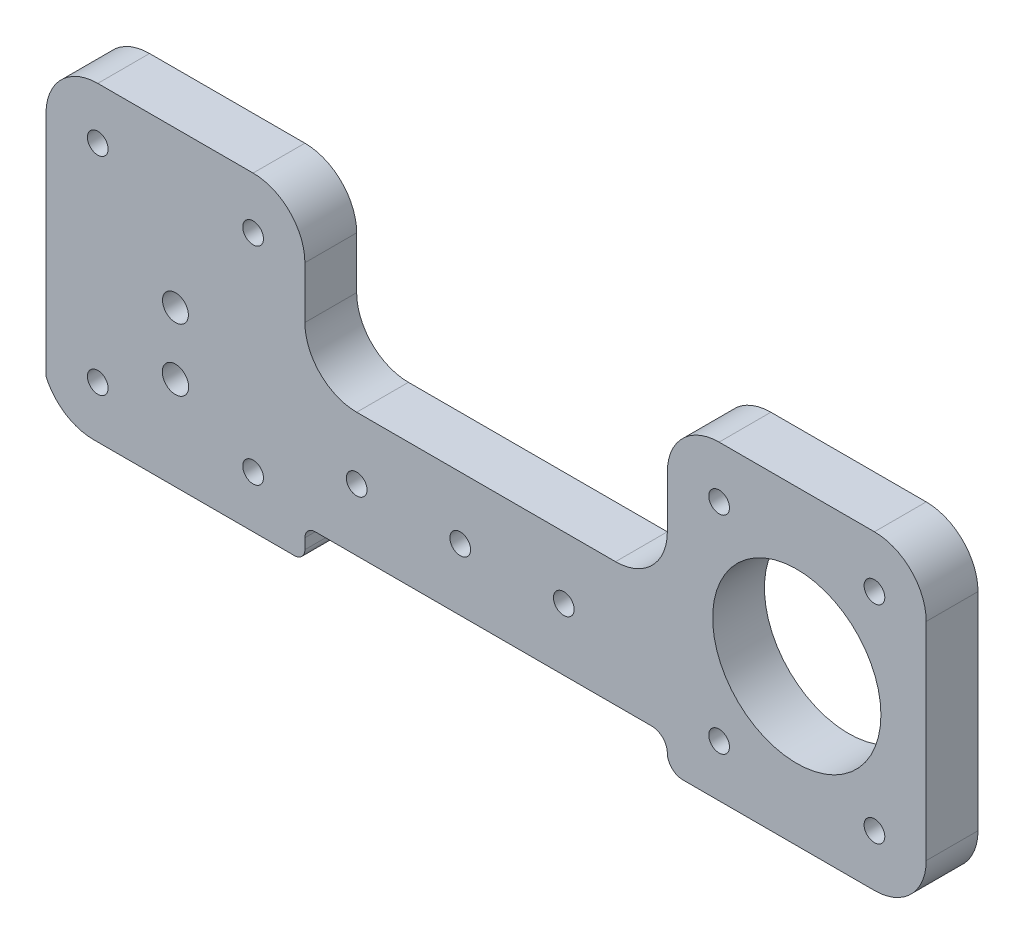
SolidWorks part; units mm, degrees
ref_plane "Front Plane" through (0, 0, 0) normal (0, 0, 1) x (1, 0, 0)
ref_plane "Top Plane" through (0, 0, 0) normal (0, 1, 0) x (1, 0, 0)
ref_plane "Right Plane" through (0, 0, 0) normal (1, 0, 0) x (0, 0, -1)
sketch "Model" plane through (0, 0, 0) normal (0, 0, 1) x (1, 0, 0)
  line L0 (-13.0894, 50) -> (-13.0894, 6)
  line L1 (26.9106, 60) -> (-3.0894, 60)
  line L2 (36.9106, 40) -> (36.9106, 50)
  line L3 (96.9106, 30) -> (46.9106, 30)
  line L4 (106.9106, 50) -> (106.9106, 40)
  line L5 (146.9106, 60) -> (116.9106, 60)
  line L6 (156.9106, 10) -> (156.9106, 50)
  line L7 (109.9106, 0) -> (146.9106, 0)
  line L8 (38.9106, 6) -> (103.9106, 6)
  line L9 (36.9106, 2) -> (36.9106, 4)
  line L10 (-3.9243, 0) -> (34.9106, 0)
  circle A0 centre (26.9106, 50) radius 2
  circle A1 centre (26.9106, 10) radius 2
  circle A2 centre (11.9106, 30) radius 2.5
  circle A3 centre (146.9106, 50) radius 2
  circle A4 centre (86.9106, 18) radius 2
  circle A5 centre (146.9106, 10) radius 2
  circle A6 centre (116.9106, 10) radius 2
  circle A7 centre (46.9106, 18) radius 2
  circle A8 centre (66.9106, 18) radius 2
  circle A9 centre (116.9106, 50) radius 2
  circle A10 centre (11.9106, 18) radius 2.55
  circle A11 centre (-3.0894, 10) radius 2
  circle A12 centre (-3.0894, 50) radius 2
  circle A13 centre (131.9106, 30) radius 16.25
  arc A14 (-3.0894, 60) -> (-13.0894, 50) centre (-3.0894, 50) ccw
  arc A15 (36.9106, 50) -> (26.9106, 60) centre (26.9106, 50) ccw
  arc A16 (36.9106, 40) -> (46.9106, 30) centre (46.9106, 40) ccw
  arc A17 (96.9106, 30) -> (106.9106, 40) centre (96.9106, 40) ccw
  arc A18 (116.9106, 60) -> (106.9106, 50) centre (116.9106, 50) ccw
  arc A19 (156.9106, 50) -> (146.9106, 60) centre (146.9106, 50) ccw
  arc A20 (146.9106, 0) -> (156.9106, 10) centre (146.9106, 10) ccw
  arc A21 (106.9106, 3) -> (109.9106, 0) centre (109.9106, 3) ccw
  arc A22 (106.9106, 3) -> (103.9106, 6) centre (103.9106, 3) ccw
  arc A23 (38.9106, 6) -> (36.9106, 4) centre (38.9106, 4) ccw
  arc A24 (34.9106, 0) -> (36.9106, 2) centre (34.9106, 2) ccw
  arc A25 (-13.0894, 6) -> (-3.9243, 0) centre (-3.9243, 10) ccw
extrude "Boss-Extrude1" add sketch "Model" along normal blind 10
sketch "Sketch2" plane through (0, 0, 10) normal (0, 0, 1) x (1, 0, 0)
  text T0 "Copyright © Adarsh Belavatagi and Manikanta Pujar 2018.\r\nThis documentation describes Open Hardware and is licensed under the CERN OHL v. 1.2.\r\nYou may redistribute and modify this documentation under the terms of the CERN OHL v.1.2.\r\n(http://ohwr.org/cernohl). This documentation is distributed WITHOUT ANY EXPRESS OR\r\nIMPLIED WARRANTY, INCLUDING OF MERCHANTABILITY, SATISFACTORY QUALITY AND FITNESS FOR A PARTICULAR PURPOSE.\r\nPlease see the CERN OHL v.1.2 for applicable conditions\r\n\r\nThe full text of the license is available in LICENSE.txt(https://github.com/AdarshBelavatagi/Maudslay/blob/master/LICENSE.txt)\r\n\r\n"
